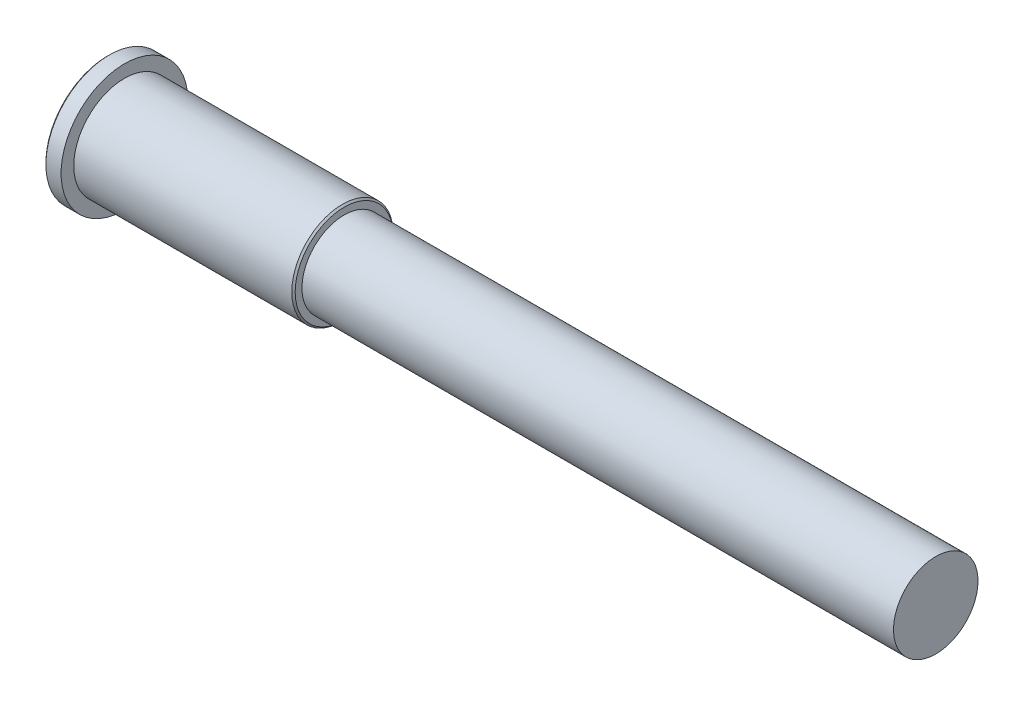
SolidWorks part; units mm, degrees
ref_plane "Front Plane" through (0, 0, 0) normal (0, 0, 1) x (1, 0, 0)
ref_plane "Top Plane" through (0, 0, 0) normal (0, 1, 0) x (1, 0, 0)
ref_plane "Right Plane" through (0, 0, 0) normal (1, 0, 0) x (0, 0, -1)
sketch "Sketch1" plane through (0, 0, 0) normal (1, 0, 0) x (0, 0, -1)
  circle A0 centre (0, 0) radius 7.5
  dimension "D1" = 15
extrude "Boss-Extrude1" add sketch "Sketch1" along normal blind 2
sketch "Sketch2" plane through (2, 0, 0) normal (1, 0, 0) x (0, 0, -1)
  circle A0 centre (0, 0) radius 6
  dimension "D1" = 12
extrude "Boss-Extrude2" add sketch "Sketch2" along normal blind 26
sketch "Sketch3" plane through (28, 0, 0) normal (1, 0, 0) x (0, 0, -1)
  circle A0 centre (0, 0) radius 5
  dimension "D1" = 10
extrude "Boss-Extrude3" add sketch "Sketch3" along normal blind 70
chamfer "Chamfer1" distance 0.2 angle 45 2 edges at (28, 0, -6) (0, 0, -7.5)
